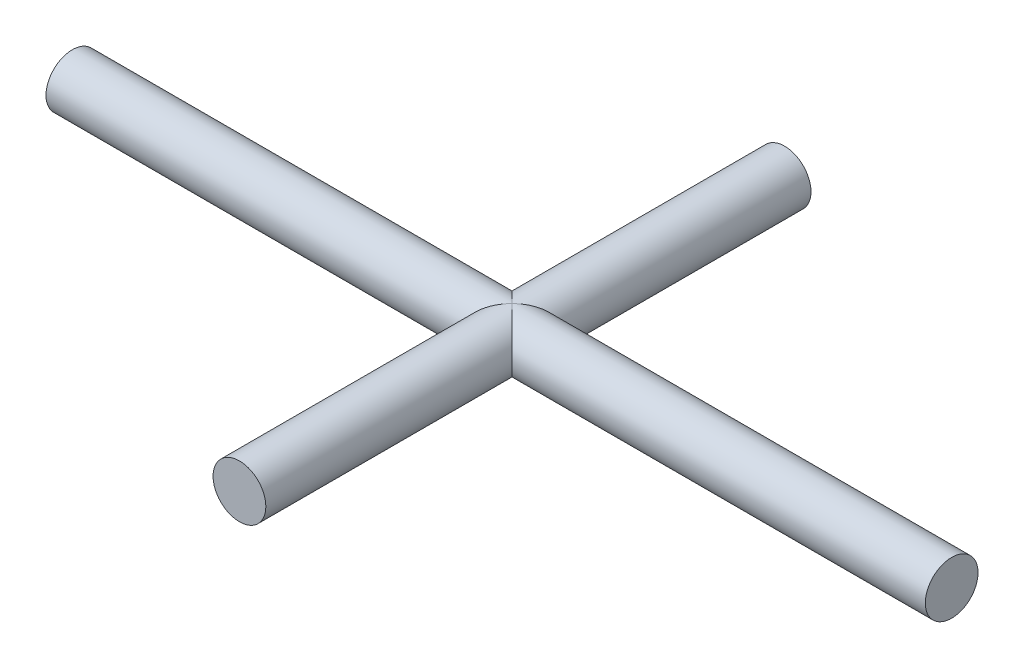
SolidWorks part; units mm, degrees
ref_plane "前视" through (0, 0, 0) normal (0, 0, 1) x (1, 0, 0)
ref_plane "上视" through (0, 0, 0) normal (0, 1, 0) x (1, 0, 0)
ref_plane "右视" through (0, 0, 0) normal (1, 0, 0) x (0, 0, -1)
sketch "草图1" plane through (0, 0, 0) normal (0, 0, 1) x (1, 0, 0)
  line L0 (-50, 0) -> (50, 0)
  line L2 (50, 0) -> (50, 3)
  line L3 (50, 3) -> (-50, 3)
  line L4 (-50, 0) -> (-50, 3)
  point P0 (0, 0)
  dimension "D1" = 100
  dimension "D2" = 50
  dimension "D3" = 3
revolve "旋转1" add sketch "草图1" angle 360 about L0
sketch "草图2" plane through (0, 0, 0) normal (1, 0, 0) x (0, 0, -1)
  line L0 (-31, 0) -> (31, 0)
  line L1 (31, 0) -> (31, 3)
  line L2 (31, 3) -> (-31, 3)
  line L3 (0, 0) -> (0, 6.1622) construction
  line L4 (-31, 0) -> (-31, 3)
  point P9 (0, 3)
  dimension "D1" = 62
  dimension "D2" = 3
revolve "旋转3" add sketch "草图2" angle 360 about L0
